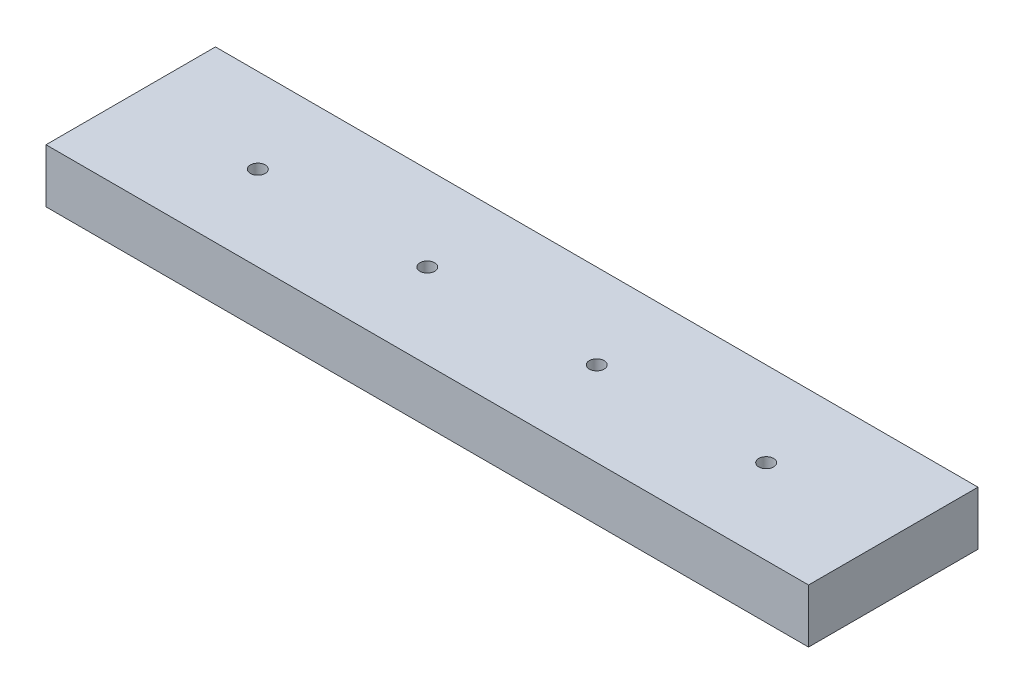
SolidWorks part; units mm, degrees
ref_plane "Front Plane" through (0, 0, 0) normal (0, 0, 1) x (1, 0, 0)
ref_plane "Top Plane" through (0, 0, 0) normal (0, 1, 0) x (1, 0, 0)
ref_plane "Right Plane" through (0, 0, 0) normal (1, 0, 0) x (0, 0, -1)
sketch "Sketch1" plane through (0, 0, 0) normal (0, 1, 0) x (1, 0, 0)
  line L0 (0, 17.6316) -> (0, -17.4211) construction
  line L1 (-25.0526, 0) -> (28.9474, 0) construction
  line L3 (45, -10) -> (-45, -10)
  line L4 (45, -10) -> (45, 10)
  line L5 (45, 10) -> (-45, 10)
  line L6 (-45, -10) -> (-45, 10)
  line L7 (45, -10) -> (-45, 10) construction
  line L8 (45, 10) -> (-45, -10) construction
  point P1 (0, 0)
  dimension "D1" = 20
  dimension "D2" = 90
extrude "Boss-Extrude1" add sketch "Sketch1" along normal blind 6.35
hole_wizard "Tap Drill for M2.2x0.45 Tap1" positions "Sketch3" profile "Sketch2" hole size "M2.2x0.45" standard "ANSI Metric" end condition through all
sketch "Sketch3" plane through (0, 6.35, 0) normal (0, 1, 0) x (1, 0, 0)
  line L0 (0, 31.8689) -> (0, -32.7453) construction
  line L2 (45, 10) -> (-45, 10) construction
  point P0 (-30, 0)
  point P2 (-10, 0)
  point P14 (30, 0)
  point P15 (10, 0)
  dimension "D1" = 20
  dimension "D2" = 20
  dimension "D3" = 10
  dimension "D4" = 10
sketch "Sketch2" plane through (-30, 6.35, 0) normal (1, 0, 0) x (0, 0, 1)
  line L0 (0, 0) -> (0, 6.35)
  line L1 (0, 6.35) -> (0.875, 6.35)
  line L2 (0.875, 6.35) -> (0.875, 0)
  line L5 (0.875, 0) -> (0, 0)
  line L11 (0, -6.35) -> (0, 107.95) construction
  dimension "Thru Hole Dia." = 1.75
  dimension "Thru Hole Depth" = 6.35
equation "\"D4@Sketch3\"=\"D3@Sketch3\""
equation "\"connector_D1\" = 70 'the big holes diameter"
equation "\"mtg_hole_D\" = 5.5 'mounting holes"
equation "\"mtg_dfc\" = 40 'mounting hole distance from center"
equation "\"plate_thickness\" = 6.35 'thickness of the plate "
equation "\"t_height\" = 200"
equation "\"t_width\" = 240"
equation "\"t_length\" = 240"
equation "\"plate_hole_from_edge\" = 9"
equation "\"plate_spacing\" = 1"
equation "\"front_plate_height\" = \"t_height\" + 38"
equation "\"front_plate_width\" = \"t_width\" + 38"
equation "\"side_plate_height\" = \"front_plate_height\""
equation "\"side_plate_length\" = \"t_length\" + 38"
equation "\"top_plate_width\" = \"front_plate_width\""
equation "\"top_plate_length\" = \"side_plate_length\""
equation "\"itx_support_t_slot_length\" = \"t_width\" + (2 * 20.5)"
equation "\"locomotion_length\" = \"t_length\""
equation "\"locomotion_width\" = \"t_width\""
equation "\"locomotion_height\" = 40"
equation "\"itx_mtg_hole_spacing\" = 40"
equation "\"D1@Boss-Extrude1\"=\"plate_thickness\""
